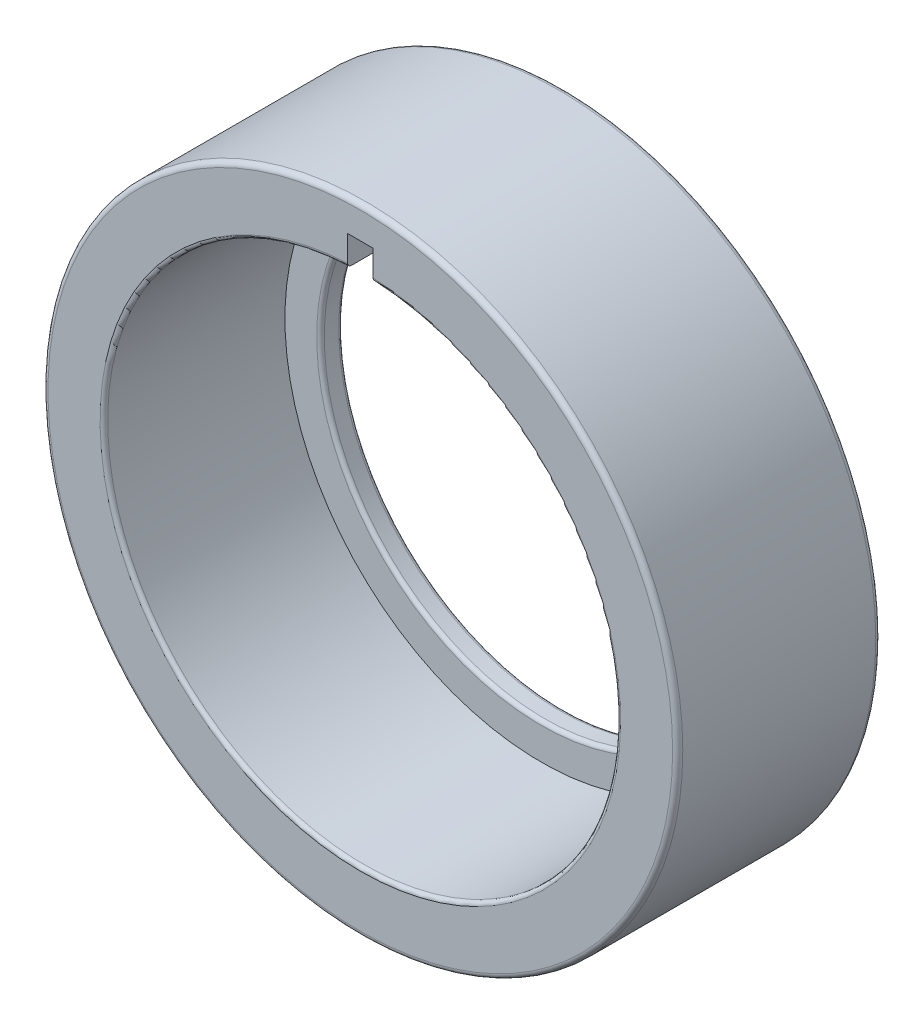
SolidWorks part; units mm, degrees
material "Gomma"
ref_plane "Piano frontale" through (0, 0, 0) normal (0, 0, 1) x (1, 0, 0)
ref_plane "Piano superiore" through (0, 0, 0) normal (0, 1, 0) x (1, 0, 0)
ref_plane "Piano destro" through (0, 0, 0) normal (1, 0, 0) x (0, 0, -1)
sketch "Schizzo1" plane through (0, 0, 0) normal (0, 0, 1) x (1, 0, 0)
  circle A0 centre (0, 0) radius 125
  circle A1 centre (0, 0) radius 101
  dimension "D1" = 250
  dimension "D2" = 202
extrude "Estrusione-Estrusione1" add sketch "Schizzo1" along normal blind 80
fillet "Raccordo1" radius 2 2 edges at (125, 0, 0) (125, 0, 80)
sketch "Schizzo3" plane through (0, 0, 0) normal (0, 0, 1) x (1, 0, 0)
  circle A0 centre (0, 0) radius 87
  circle A1 centre (0, 0) radius 101 construction
  circle A2 centre (0, 0) radius 101
  dimension "D1" = 174
extrude "Estrusione-Estrusione2" add sketch "Schizzo3" along normal blind 8.7
fillet "Raccordo2" radius 1.5 3 edges at (87, 0, 8.7) (87, 0, 0) (101, 0, 80)
sketch "Schizzo6" plane through (0, 0, 0) normal (0, 0, -1) x (-1, 0, 0)
  line L0 (0, -1000) -> (0, 49000) construction
  line L1 (-1000, 0) -> (49000, 0) construction
  point P8 (96, 0)
  point P9 (0, -96)
  point P10 (-96, 0)
  point P11 (0, 96)
  dimension "D1" = 4
  dimension "D2" = 96
  dimension "D3" = 96
  dimension "D4" = 96
ref_plane "Piano2" through (0, -125, 0) normal (0, -1, 0) x (-1, 0, 0)
ref_plane "Piano3" through (0, 0, 40) normal (0, 0, 1) x (1, 0, 0)
sketch "Schizzo13" plane through (0, 0, 40) normal (0, 0, 1) x (1, 0, 0)
  line L0 (0, -1000) -> (0, 49000) construction
sketch "Schizzo14" plane through (0, 0, 80) normal (0, 0, 1) x (1, 0, 0)
  line L0 (0, -1000) -> (0, 49000) construction
  line L2 (-5, 112.5) -> (5, 112.5)
  line L3 (-5, 112.5) -> (-5, 77.5)
  line L4 (-5, 77.5) -> (5, 77.5)
  line L5 (5, 112.5) -> (5, 77.5)
  line L6 (-5, 112.5) -> (5, 77.5) construction
  line L7 (-5, 77.5) -> (5, 112.5) construction
  circle A0 centre (0, 0) radius 125 construction
  point P1 (0, 95)
  dimension "D1" = 10
  dimension "D2" = 95
  dimension "D3" = 35
extrude "Taglio-Estrusione1" cut sketch "Schizzo14" against normal up to surface (71.3 mm away) up to face at (88.5, 0, 8.7)
